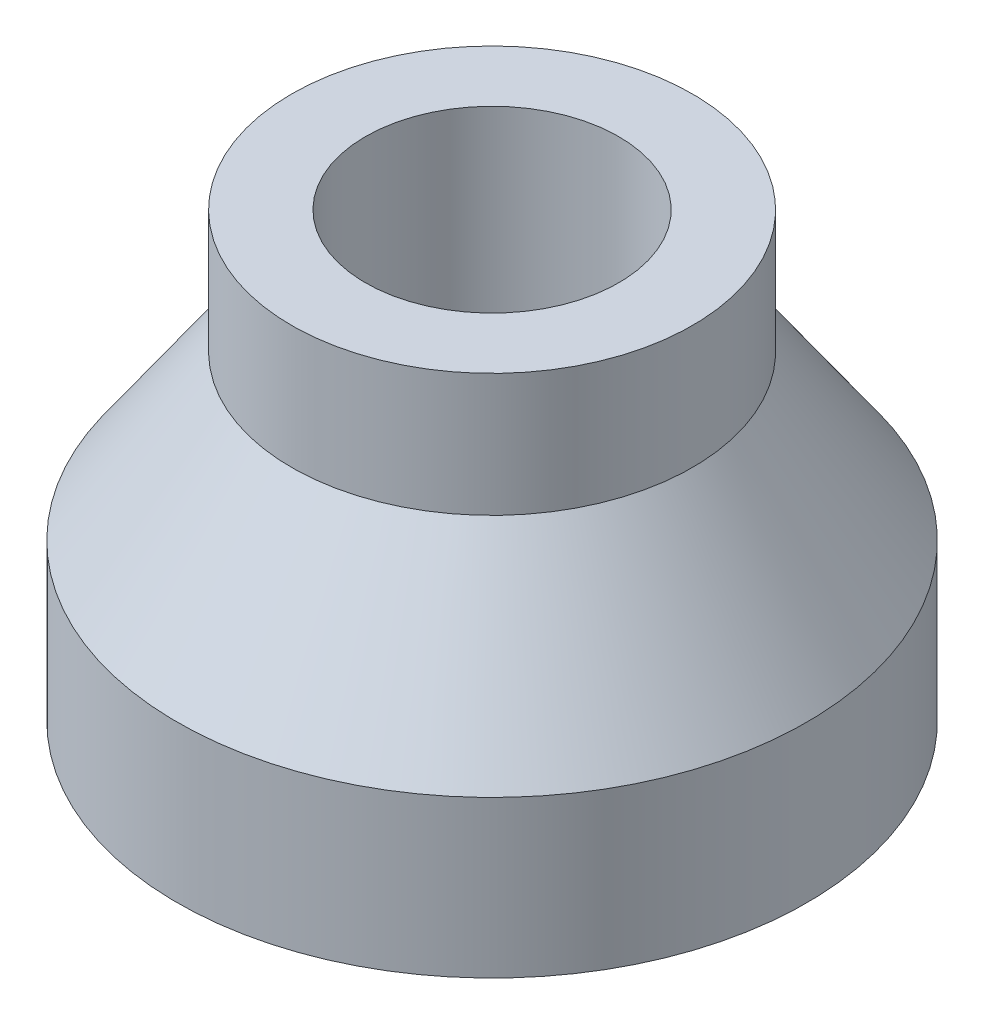
SolidWorks part; units mm, degrees
material "POM 乙缩醛共聚物"
ref_plane "前视基准面" through (0, 0, 0) normal (0, 0, 1) x (1, 0, 0)
ref_plane "上视基准面" through (0, 0, 0) normal (0, 1, 0) x (1, 0, 0)
ref_plane "右视基准面" through (0, 0, 0) normal (1, 0, 0) x (0, 0, -1)
sketch "草图1" plane through (0, 0, 0) normal (0, 0, 1) x (1, 0, 0)
  line L0 (-10, -0.1256) -> (-10, -70.7346) construction
  line L1 (-12.575, -21.0098) -> (-14.075, -21.0098)
  line L2 (-14.075, -21.0098) -> (-14.075, -23.5098)
  line L3 (-14.075, -23.5098) -> (-16.4, -26.8302)
  line L4 (-16.4, -26.8302) -> (-16.4, -30.0098)
  line L5 (-16.4, -30.0098) -> (-14.4, -30.0098)
  line L6 (-14.4, -30.0098) -> (-14.4, -27.4608)
  line L7 (-14.4, -27.4608) -> (-12.575, -24.8545)
  line L8 (-12.575, -24.8545) -> (-12.575, -21.0098)
  line L9 (-10, -17) -> (-10, -2) construction
  dimension "D1" = 1.5
  dimension "D2" = 2
  dimension "D3" = 2
  dimension "D4" = 2.5
  dimension "D5" = 35
  dimension "D6" = 5.15
  dimension "D7" = 12.8
revolve "旋转1" add sketch "草图1" angle 360 about L0
